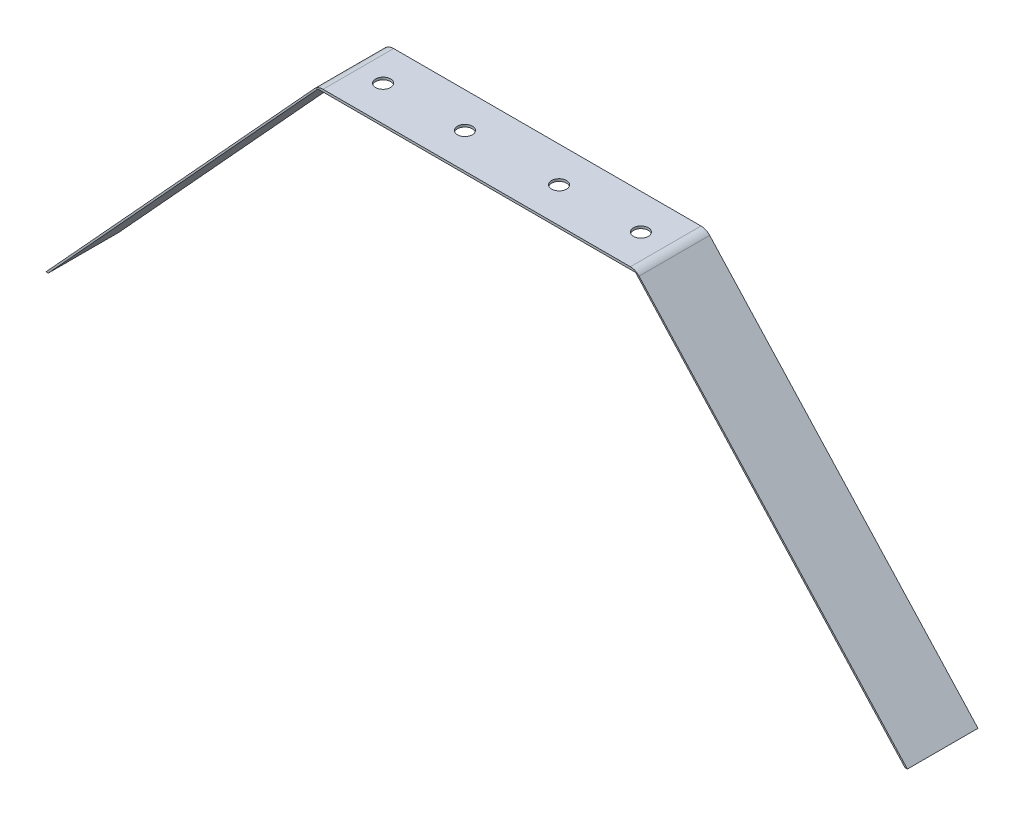
SolidWorks part; units mm, degrees
material "Thornel Mat VMA"
ref_plane "Front Plane" through (0, 0, 0) normal (0, 0, 1) x (1, 0, 0)
ref_plane "Top Plane" through (0, 0, 0) normal (0, 1, 0) x (1, 0, 0)
ref_plane "Right Plane" through (0, 0, 0) normal (1, 0, 0) x (0, 0, -1)
sketch "Sketch1" plane through (0, 0, 0) normal (0, 0, 1) x (1, 0, 0)
  line L1 (-205, 97.5) -> (205, 97.5)
  line L2 (-205, 97.5) -> (-205, -97.5)
  line L3 (-205, -97.5) -> (205, -97.5)
  line L4 (205, 97.5) -> (205, -97.5)
  line L5 (-205, 97.5) -> (205, -97.5) construction
  line L6 (-205, -97.5) -> (205, 97.5) construction
  point P0 (0, 0)
extrude "Boss-Extrude1" add sketch "Sketch1" along normal blind 30
sketch "Sketch2" plane through (0, 0, 30) normal (0, 0, 1) x (1, 0, 0)
  line L1 (-205, 97.5) -> (-205, -97.5) construction
  line L5 (205, 97.5) -> (-205, 97.5) construction
  line L8 (-205, -52.5) -> (-205, -97.5)
  line L9 (205, -97.5) -> (205, 97.5) construction
  line L10 (205, -52.5) -> (67.5, 97.5)
  line L11 (-205, -52.5) -> (-67.5, 97.5)
  line L12 (-205, -97.5) -> (205, -97.5)
  line L13 (205, -52.5) -> (67.5, 97.5)
  line L15 (205, -97.5) -> (205, -52.5)
  line L16 (67.5, 97.5) -> (-67.5, 97.5)
  line M13 (205, -97.5) -> (205, 97.5)
  line M14 (205, 97.5) -> (-205, 97.5)
  line M15 (-205, 97.5) -> (-205, -97.5)
extrude "Cut-Extrude1" cut sketch "Sketch2" against normal blind 30 contours L11 M15 M14 | L10 M13 M14
sketch "Sketch3" plane through (0, 0, 30) normal (0, 0, 1) x (1, 0, 0)
  line L0 (-205, -97.5) -> (-204, -97.5)
  line L1 (-205, -97.5) -> (205, -97.5) construction
  line L3 (-204, -52.5) -> (-40.8942, 125.5423)
  line L5 (-204, -97.5) -> (-204, -52.5)
  line L6 (-67.5, 97.5) -> (-67.5, 96.5)
  line L7 (-67.5, 96.5) -> (67.5, 96.5)
  line L8 (67.5, 97.5) -> (67.5, 96.5)
  line L10 (205, -97.5) -> (204, -97.5)
  line L11 (204, -97.5) -> (204, -52.5)
  line L12 (204, -52.5) -> (67.5, 96.5)
  line M7 (-205, -97.5) -> (205, -97.5)
extrude "Cut-Extrude2" cut sketch "Sketch3" against normal blind 30 contours L11 L12 L7 L3 L5 M7
fillet "Fillet1" radius 5 1 edges at (-205, -52.5, 15)
fillet "Fillet4" radius 5 1 edges at (-67.5, 97.5, 15)
fillet "Fillet5" radius 5 1 edges at (67.5, 97.5, 15)
fillet "Fillet6" radius 5 1 edges at (205, -52.5, 15)
ref_plane "Plane1" through (205, 0, 0) normal (1, 0, 0) x (0, 0, -1)
sketch "Sketch4" plane through (205, 0, 0) normal (1, 0, 0) x (0, 0, -1)
  line L0 (-15, -97.5) -> (-15, -52.2848) construction
  line L1 (-30, -97.5) -> (0, -97.5) construction
  line L2 (-30, -75.9725) -> (0, -75.9725) construction
  line L5 (-30, -97.5) -> (-30, -54.4449) construction
  line L6 (0, -97.5) -> (0, -54.4449) construction
  circle A0 centre (-15, -75.9725) radius 1.65
  dimension "D1" = 3.3
extrude "Cut-Extrude3" cut sketch "Sketch4" against normal through all
ref_plane "Plane2" through (0, 97.5, 0) normal (0, 1, 0) x (1, 0, 0)
sketch "Sketch5" plane through (0, 97.5, 0) normal (0, 1, 0) x (1, 0, 0)
  line L0 (-64.4681, -15) -> (64.4681, -15) construction
  line L1 (-67.5, -30) -> (67.5, -30) construction
  line L3 (0, 0) -> (0, -30) construction
  circle A2 centre (-20, -15) radius 3.175
  circle A3 centre (20, -15) radius 3.175
  circle A4 centre (54.7688, -15) radius 3.175
  circle A5 centre (-54.7687, -15) radius 3.175
  point P17 (0, -15)
  point P18 (0, -15)
  dimension "D1" = 6.35
  dimension "D2" = 6.35
  dimension "D3" = 20
  dimension "D5" = 6.35
  dimension "D6" = 6.35
  dimension "D4" = 20
  dimension "D7" = 109.5375
  dimension "D8" = 34.7688
extrude "Cut-Extrude4" cut sketch "Sketch5" against normal blind 10
ref_plane "Plane3" through (210, 0, 0) normal (1, 0, 0) x (0, 0, -1)
sketch "Sketch7" plane through (210, 0, 0) normal (1, 0, 0) x (0, 0, -1)
  line L2 (0, -51.0663) -> (0, 95.8786) construction
  line L4 (-30, -51.0663) -> (-30, 95.8786) construction
  line L6 (-30, -28.5) -> (-30, -97.5)
  line L7 (-30, -97.5) -> (0, -97.5)
  line L8 (0, -97.5) -> (0, -28.5)
  line L9 (-30, -28.5) -> (0, -28.5)
extrude "Cut-Extrude6" cut sketch "Sketch7" against normal blind 420
